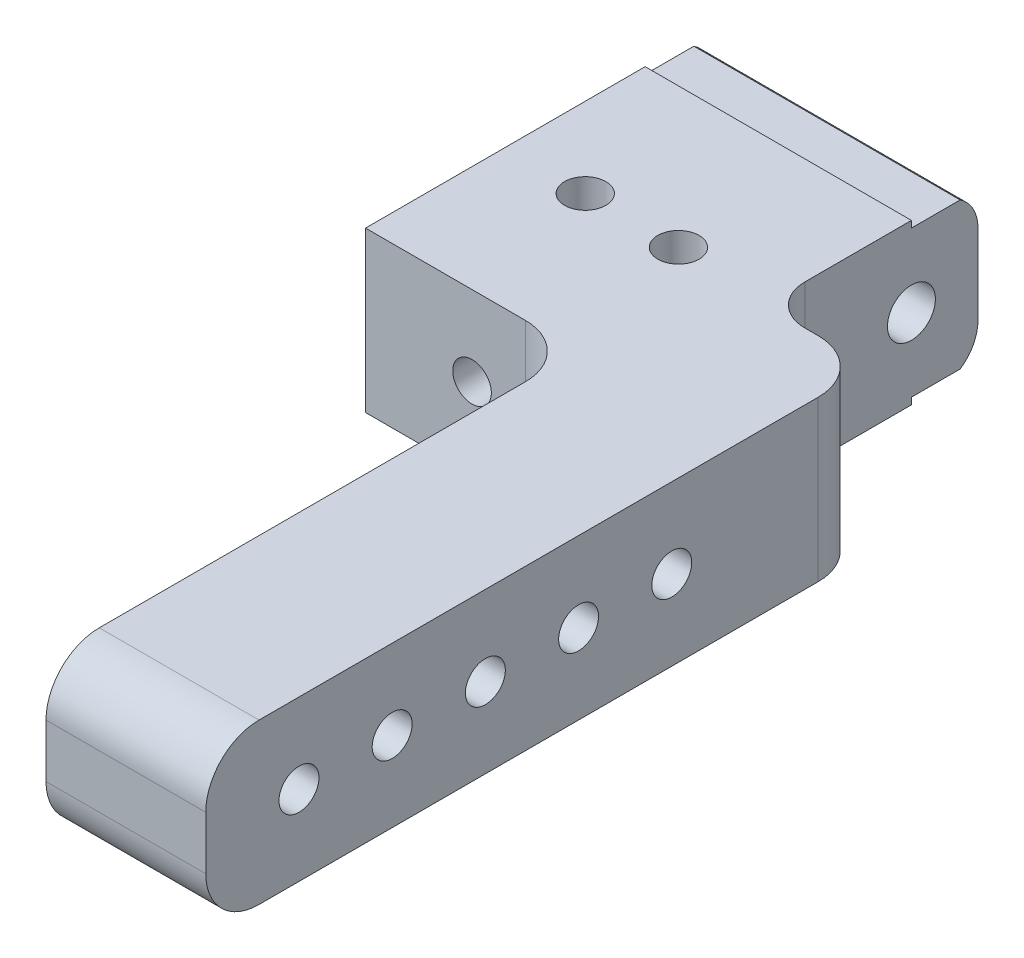
SolidWorks part; units mm, degrees
ref_plane "Front" through (0, 0, 0) normal (0, 0, 1) x (1, 0, 0)
ref_plane "Top" through (0, 0, 0) normal (0, 1, 0) x (1, 0, 0)
ref_plane "Right" through (0, 0, 0) normal (1, 0, 0) x (0, 0, -1)
sketch "Sketch1" plane through (0, 0, 0) normal (0, 0, 1) x (1, 0, 0)
  line L1 (0, 0) -> (20, 0)
  line L2 (0, 0) -> (0, -12)
  line L3 (0, -12) -> (20, -12)
  line L4 (20, 0) -> (20, -12)
  dimension "D1" = 20
  dimension "D2" = 12
extrude "Boss-Extrude1" add sketch "Sketch1" along normal blind 26
sketch "Sketch2" plane through (20, 0, 0) normal (1, 0, 0) x (0, 0, -1)
  line L0 (-26, 0) -> (0, 0) construction
  line L1 (-26, -12) -> (-16, -12)
  line L2 (-26, -12) -> (-26, 0)
  line L3 (-26, 0) -> (-16, 0)
  line L4 (-16, -12) -> (-16, 0)
  dimension "D1" = 10
extrude "Boss-Extrude2" add sketch "Sketch2" along normal blind 8
sketch "Sketch4" plane through (0, 0, 0) normal (0, 1, 0) x (1, 0, 0)
  line L0 (28, -26) -> (0, -26) construction
  line L1 (0, -26) -> (0, 0) construction
  circle A0 centre (13, -15.5) radius 1.55
  circle A1 centre (6, -15.5) radius 1.55
  dimension "D1" = 3.1
  dimension "D2" = 3.1
  dimension "D3" = 7
  dimension "D4" = 10.5
  dimension "D5" = 6
  dimension "D6" = 10.5
extrude "Cut-Extrude2" cut sketch "Sketch4" against normal through all
fillet "Fillet1" radius 3 1 edges at (20, -6, 16)
fillet "Fillet3" radius 3 2 edges at (10, -12, 0) (10, 0, 0)
sketch "Sketch5" plane through (0, 0, 0) normal (-1, 0, 0) x (0, 0, 1)
  line L0 (26, -12) -> (3, -12) construction
  line L1 (5, -12) -> (-4.9767, -12)
  line L2 (5, -12) -> (5, -11.5)
  line L3 (5, -11.5) -> (-4.9767, -11.5)
  line L4 (-4.9767, -12) -> (-4.9767, -11.5)
  line L5 (26, 0) -> (3, 0) construction
  line L6 (5, 0) -> (-7.2599, 0)
  line L7 (5, 0) -> (5, -0.5)
  line L8 (5, -0.5) -> (-7.2599, -0.5)
  line L9 (-7.2599, 0) -> (-7.2599, -0.5)
  line L10 (0, -3) -> (0, -9) construction
  dimension "D1" = 0.5
  dimension "D2" = 0.5
  dimension "D3" = 5
  dimension "D4" = 5
extrude "Cut-Extrude3" cut sketch "Sketch5" against normal through all
sketch "Sketch6" plane through (0, 0, 0) normal (0, 0, -1) x (-1, 0, 0)
  line L1 (-12.75, 7.3758) -> (-7.25, 7.3758)
  line L2 (-12.75, 7.3758) -> (-12.75, -23.1123)
  line L3 (-12.75, -23.1123) -> (-7.25, -23.1123)
  line L4 (-7.25, 7.3758) -> (-7.25, -23.1123)
  dimension "D1" = 5.5
  dimension "D2" = 7.25
extrude "Cut-Extrude4" cut sketch "Sketch6" against normal blind 0.8
sketch "Sketch8" plane through (0, 0, 26) normal (0, 0, 1) x (1, 0, 0)
  line L0 (28, 0) -> (0, 0) construction
  line L1 (28, -12) -> (16, -12)
  line L2 (28, -12) -> (28, 0)
  line L3 (28, 0) -> (16, 0)
  line L4 (16, -12) -> (16, 0)
  dimension "D1" = 12
extrude "Boss-Extrude3" add sketch "Sketch8" along normal blind 40
sketch "Sketch3" plane through (0, 0, 0) normal (-1, 0, 0) x (0, 0, 1)
  line L0 (0, -3) -> (0, -9) construction
  line L2 (26, -12) -> (5, -12) construction
  circle A0 centre (5, -6) radius 1.8
  dimension "D1" = 3.6
  dimension "D2" = 5
  dimension "D6" = 6
extrude "Cut-Extrude1" cut sketch "Sketch3" against normal through all
sketch "Sketch9" plane through (28, 0, 0) normal (1, 0, 0) x (0, 0, -1)
  line L0 (-16, -12) -> (-16, 0) construction
  circle A0 centre (-31, -6) radius 1.5
  circle A1 centre (-38, -6) radius 1.5
  circle A2 centre (-45, -6) radius 1.5
  circle A3 centre (-52, -6) radius 1.5
  circle A4 centre (-59, -6) radius 1.5
  dimension "D1" = 3
  dimension "D2" = 15
  dimension "D3" = 5
extrude "Cut-Extrude6" cut sketch "Sketch9" against normal blind 12
fillet "Fillet4" radius 4 1 edges at (16, -6, 26)
sketch "Sketch10" plane through (0, 0, 26) normal (0, 0, 1) x (1, 0, 0)
  line L0 (0, 0) -> (0, -12) construction
  circle A0 centre (8, -6) radius 1.45
  dimension "D1" = 2.9
  dimension "D2" = 8
extrude "Cut-Extrude7" cut sketch "Sketch10" against normal blind 12
fillet "Fillet5" radius 4 1 edges at (28, -6, 16)
fillet "Fillet7" radius 4 2 edges at (22, -12, 66) (22, 0, 66)
equation "\"滑动-垂直孔\" = 0.6"
equation "\"滑动-水平孔\"= 0.3"
equation "\"松动-垂直孔\" = 0.3"
equation "\"松动-水平孔\"= 0.1"
equation "\"正常-垂直孔\" = 0.15"
equation "\"正常-水平孔\"= 0"
equation "\"紧缩-垂直孔\"= 0"
equation "\"紧缩-水平孔\"= - 0.1"
equation "\"D1@Sketch3\"=\"滑动-垂直孔\"+3"
equation "\"D2@Sketch4\"=\"松动-水平孔\"+3"
equation "\"D1@Sketch4\"=\"松动-水平孔\"+3"
equation "\"D1@Sketch10\"=\"紧缩-水平孔\"+3"
equation "\"D1@Sketch9\"=\"紧缩-垂直孔\"+3"
